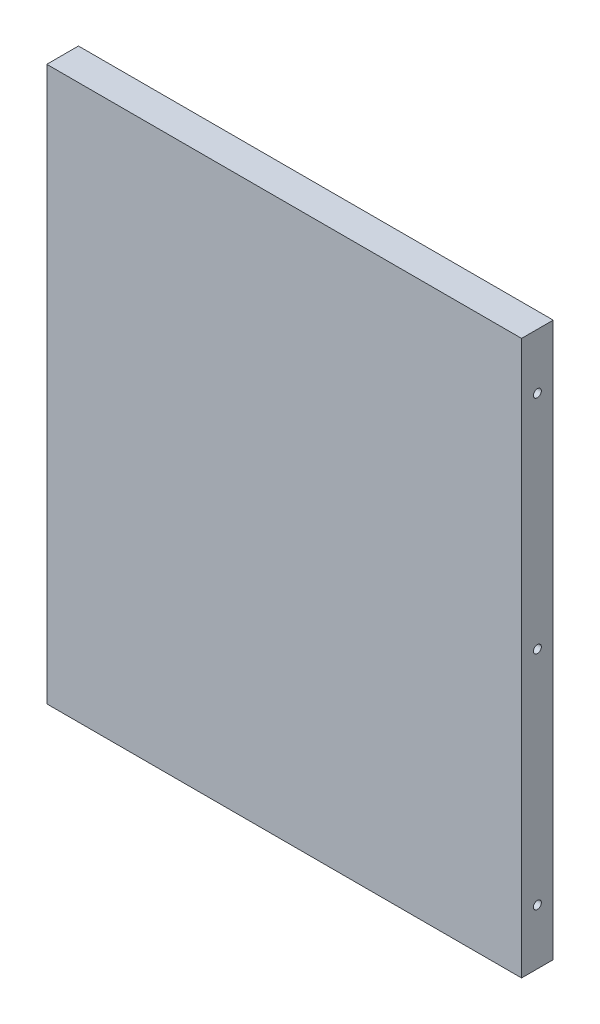
SolidWorks part; units mm, degrees
ref_plane "Ebene vorne" through (0, 0, 0) normal (0, 0, 1) x (1, 0, 0)
ref_plane "Ebene oben" through (0, 0, 0) normal (0, 1, 0) x (1, 0, 0)
ref_plane "Ebene rechts" through (0, 0, 0) normal (1, 0, 0) x (0, 0, -1)
sketch "Skizze1" plane through (0, 0, 0) normal (0, 0, 1) x (1, 0, 0)
  line L1 (-84.7009, 65.5769) -> (65.2991, 65.5769)
  line L2 (-84.7009, 65.5769) -> (-84.7009, -109.4231)
  line L3 (-84.7009, -109.4231) -> (65.2991, -109.4231)
  line L4 (65.2991, 65.5769) -> (65.2991, -109.4231)
  dimension "D1" = 150
  dimension "D2" = 175
extrude "Aufsatz-Linear austragen1" add sketch "Skizze1" along normal blind 10
sketch "Skizze2" plane through (-84.7009, 0, 0) normal (-1, 0, 0) x (0, 0, 1)
  line L0 (0, -21.9231) -> (10, -21.9231) construction
  line L1 (0, 65.5769) -> (0, -109.4231) construction
  line L2 (10, 65.5769) -> (10, -109.4231) construction
  line L3 (5, -91.9231) -> (5, -21.9231) construction
  line L4 (5, -21.9231) -> (5, 48.0769) construction
  circle A0 centre (5, 48.0769) radius 1.25
  circle A1 centre (5, -21.9231) radius 1.25
  circle A3 centre (5, -91.9231) radius 1.25
  point P6 (5, -21.9231)
  point P11 (5, -21.9231)
  dimension "D2" = 2.5
  dimension "D1" = 70
extrude "Schnitt-Linear austragen1" cut sketch "Skizze2" against normal blind 5
sketch "Skizze3" plane through (65.2991, 0, 0) normal (1, 0, 0) x (0, 0, -1)
  line L0 (-10, -21.9231) -> (0, -21.9231) construction
  line L1 (-5, -91.9231) -> (-5, -21.9231) construction
  line L2 (-5, -21.9231) -> (-5, 48.0769) construction
  line L4 (0, -109.4231) -> (0, 65.5769) construction
  line L5 (-10, -109.4231) -> (-10, 65.5769) construction
  circle A0 centre (-5, 48.0769) radius 1.25
  circle A1 centre (-5, -21.9231) radius 1.25
  circle A3 centre (-5, -91.9231) radius 1.25
  point P2 (-5, -21.9231)
  point P7 (-5, -21.9231)
  dimension "D2" = 2.5
  dimension "D1" = 70
extrude "Schnitt-Linear austragen2" cut sketch "Skizze3" against normal blind 5
